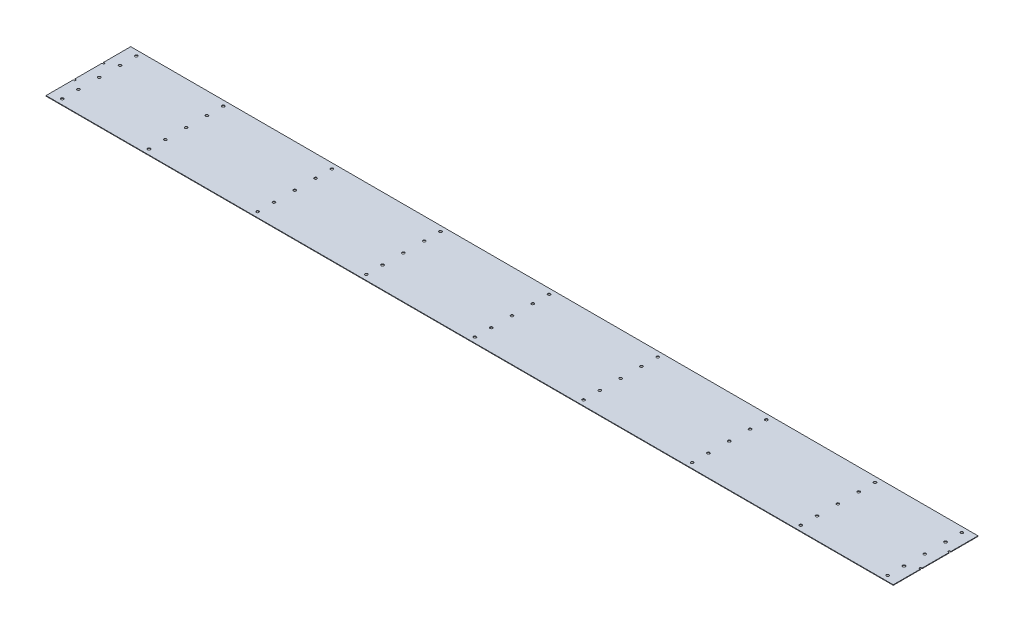
SolidWorks part; units mm, degrees
ref_plane "Front Plane" through (0, 0, 0) normal (0, 0, 1) x (1, 0, 0)
ref_plane "Top Plane" through (0, 0, 0) normal (0, 1, 0) x (1, 0, 0)
ref_plane "Right Plane" through (0, 0, 0) normal (1, 0, 0) x (0, 0, -1)
sketch "Sketch1" plane through (0, 0, 0) normal (0, 1, 0) x (1, 0, 0)
  line L0 (-780, -25) -> (-780, 25)
  line L1 (-780, 25) -> (780, 25) construction
  line L2 (-780, 25) -> (-780, -25) construction
  line L3 (-780, -25) -> (780, -25) construction
  line L4 (780, 25) -> (780, -25) construction
  line L5 (-780, 25) -> (780, -25) construction
  line L6 (-780, -25) -> (780, 25) construction
  line L7 (-780, 25) -> (-777, 25)
  line L8 (-777, 25) -> (-777, 28)
  line L9 (-777, 28) -> (-780, 28)
  line L10 (-780, 28) -> (-780, 78)
  line L11 (-780, 78) -> (780, 78)
  line L12 (780, 78) -> (780, 28)
  line L13 (780, 28) -> (777, 28)
  line L14 (777, 28) -> (777, 25)
  line L15 (777, 25) -> (780, 25)
  line L16 (780, 25) -> (780, -25)
  line L17 (780, -25) -> (777, -25)
  line L18 (777, -25) -> (777, -28)
  line L19 (777, -28) -> (780, -28)
  line L20 (780, -28) -> (780, -78)
  line L21 (780, -78) -> (-780, -78)
  line L22 (-780, -78) -> (-780, -28)
  line L23 (-780, -28) -> (-777, -28)
  line L24 (-777, -28) -> (-777, -25)
  line L25 (-777, -25) -> (-780, -25)
  line L26 (-777, 28) -> (777, 28) construction
  line L27 (777, -28) -> (-777, -28) construction
  line L28 (-780, 68.3) -> (780, 68.3) construction
  line L29 (0, 68.3) -> (0, -68.3) construction
  line L30 (-760, 68.3) -> (-760, -68.3) construction
  line L31 (780, 38.3) -> (-780, 38.3) construction
  line L32 (760, 68.3) -> (760, -68.3) construction
  line L34 (-780, -38.3) -> (780, -38.3) construction
  line L37 (780, -68.3) -> (-780, -68.3) construction
  circle A0 centre (0, 68.3) radius 2.45
  circle A1 centre (0, 38.3) radius 2.45
  circle A2 centre (0, -38.3) radius 2.45
  circle A3 centre (0, -68.3) radius 2.45
  circle A4 centre (0, 0) radius 2.45
  circle A5 centre (200, 68.3) radius 2.45
  circle A6 centre (200, 38.3) radius 2.45
  circle A7 centre (200, 0) radius 2.45
  circle A8 centre (200, -38.3) radius 2.45
  circle A9 centre (200, -68.3) radius 2.45
  circle A10 centre (400, 68.3) radius 2.45
  circle A11 centre (400, 38.3) radius 2.45
  circle A12 centre (400, 0) radius 2.45
  circle A13 centre (400, -38.3) radius 2.45
  circle A14 centre (400, -68.3) radius 2.45
  circle A15 centre (600, 68.3) radius 2.45
  circle A16 centre (600, 38.3) radius 2.45
  circle A17 centre (600, 0) radius 2.45
  circle A18 centre (600, -38.3) radius 2.45
  circle A19 centre (600, -68.3) radius 2.45
  circle A20 centre (-200, -68.3) radius 2.45
  circle A21 centre (-200, -38.3) radius 2.45
  circle A22 centre (-200, 0) radius 2.45
  circle A23 centre (-200, 38.3) radius 2.45
  circle A24 centre (-200, 68.3) radius 2.45
  circle A25 centre (-400, -68.3) radius 2.45
  circle A26 centre (-400, -38.3) radius 2.45
  circle A27 centre (-400, 0) radius 2.45
  circle A28 centre (-400, 38.3) radius 2.45
  circle A29 centre (-400, 68.3) radius 2.45
  circle A30 centre (-600, -68.3) radius 2.45
  circle A31 centre (-600, -38.3) radius 2.45
  circle A32 centre (-600, 0) radius 2.45
  circle A33 centre (-600, 38.3) radius 2.45
  circle A34 centre (-600, 68.3) radius 2.45
  circle A35 centre (-760, 68.3) radius 2.45
  circle A36 centre (-760, 38.3) radius 2.45
  circle A37 centre (-760, 0) radius 2.45
  circle A38 centre (-760, -68.3) radius 2.45
  circle A39 centre (-760, -38.3) radius 2.45
  circle A40 centre (760, -68.3) radius 2.45
  circle A41 centre (760, 0) radius 2.45
  circle A42 centre (760, 68.3) radius 2.45
  circle A43 centre (760, 38.3) radius 2.45
  circle A44 centre (760, -38.3) radius 2.45
  point P0 (0, 0)
  point P120 (747.9995, -38.3)
  point P121 (747.5877, -38.3)
  point P122 (760, 38.3)
  point P123 (760, -38.3)
  dimension "D10" = 4.9
  dimension "D1" = 1560
  dimension "D2" = 50
  dimension "D3" = 50
  dimension "D4" = 3
  dimension "D5" = 3
  dimension "D6" = 30
  dimension "D7" = 13.3
  dimension "D8" = 13.3
  dimension "D9" = 30
  dimension "D12" = 200
  dimension "D14" = 200
  dimension "D15" = 20
  dimension "D16" = 20
  dimension "D11" = 4
  dimension "D13" = 4
extrude "Boss-Extrude1" add sketch "Sketch1" along normal blind 1 contours L25 L24 L23 L22 L21 L20 L19 L18 L17 L16 L15 L14 L13 L12 L11 L10 L9 L8 L7 L0 A44 A43 A42 A41 A40 A39 A38 A37 A36 A35 A34 A33 A32 A31 A30
